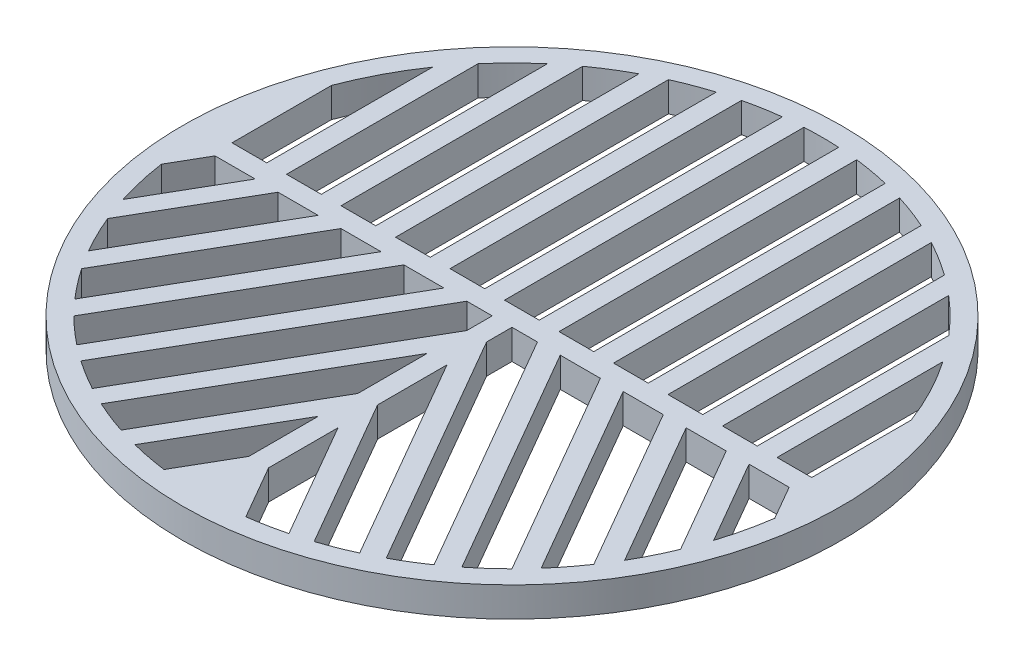
SolidWorks part; units mm, degrees
ref_plane "Front Plane" through (0, 0, 0) normal (0, 0, 1) x (1, 0, 0)
ref_plane "Top Plane" through (0, 0, 0) normal (0, 1, 0) x (1, 0, 0)
ref_plane "Right Plane" through (0, 0, 0) normal (1, 0, 0) x (0, 0, -1)
sketch "Sketch1" plane through (0, 0, 0) normal (0, 1, 0) x (1, 0, 0)
  line L0 (-33.325, 0) -> (33.325, 0) construction
  line L1 (-33.31, 1) -> (33.31, 1) construction
  line L2 (-33.31, -1) -> (33.31, -1) construction
  line L3 (0, 1) -> (0, -1) construction
  line L4 (0, 31.325) -> (0, 33.325) construction
  line L5 (1.7555, 1) -> (1.7555, 31.2758)
  line L6 (1.7555, 1) -> (-1.7555, 1)
  line L7 (-1.7555, 1) -> (-1.7555, 31.2758)
  line L8 (29.31, 1) -> (29.31, 11.0535)
  line L9 (29.31, 1) -> (25.7991, 1)
  line L10 (25.7991, 1) -> (25.7991, 17.7669)
  line L11 (3.7555, 1) -> (7.2664, 1)
  line L12 (9.2664, 1) -> (12.7773, 1)
  line L13 (14.7773, 1) -> (18.2882, 1)
  line L14 (20.2882, 1) -> (23.7991, 1)
  line L15 (3.7555, 1) -> (3.7555, 31.0991)
  line L16 (7.2664, 1) -> (7.2664, 30.4706)
  line L17 (9.2664, 1) -> (9.2664, 29.9231)
  line L18 (12.7773, 1) -> (12.7773, 28.6006)
  line L19 (14.7773, 1) -> (14.7773, 27.6204)
  line L20 (18.2882, 1) -> (18.2882, 25.4322)
  line L21 (20.2882, 1) -> (20.2882, 23.8672)
  line L22 (23.7991, 1) -> (23.7991, 20.3681)
  line L23 (25.7991, 9.3835) -> (23.7991, 9.3835) construction
  line L24 (20.2882, 9.3835) -> (18.2882, 9.3835) construction
  line L25 (14.7773, 9.3835) -> (12.7773, 9.3835) construction
  line L26 (9.2664, 9.3835) -> (7.2664, 9.3835) construction
  line L27 (3.7555, 9.3835) -> (1.7555, 9.3835) construction
  line L28 (0, -1) -> (0, -31.325) construction
  line L29 (1, -1) -> (1, -31.309) construction
  line L30 (1, -13.9187) -> (-1, -13.9187) construction
  line L31 (1, -3.5702) -> (1, -1)
  line L32 (1, -1) -> (3.5702, -1)
  line L33 (3.5702, -1) -> (17.8534, -25.7393)
  line L34 (1, -3.5702) -> (14.8598, -27.5761)
  line L35 (10.9033, -13.7014) -> (7.8628, -15.4569) construction
  line L36 (5.8796, -1) -> (19.47, -24.5393)
  line L37 (9.9336, -1) -> (22.1466, -22.1536)
  line L38 (5.8796, -1) -> (9.9336, -1)
  line L39 (10.9033, -13.7014) -> (12.6354, -12.7014) construction
  line L40 (12.6354, -12.7014) -> (15.6759, -10.946) construction
  line L41 (12.243, -1) -> (23.5748, -20.6273)
  line L42 (16.2971, -1) -> (25.8958, -17.6256)
  line L43 (18.6065, -1) -> (27.1, -15.7113)
  line L44 (22.6605, -1) -> (28.9671, -11.9233)
  line L45 (24.9699, -1) -> (29.8595, -9.4691)
  line L46 (29.024, -1) -> (31.009, -4.4382)
  line L47 (15.6759, -10.946) -> (17.408, -9.946) construction
  line L48 (17.408, -9.946) -> (20.4485, -8.1905) construction
  line L49 (20.4485, -8.1905) -> (22.1806, -7.1905) construction
  line L50 (22.1806, -7.1905) -> (25.2211, -5.4351) construction
  line L51 (25.2211, -5.4351) -> (26.9531, -4.4351) construction
  line L52 (26.9531, -4.4351) -> (29.9937, -2.6796) construction
  line L53 (12.243, -1) -> (16.2971, -1)
  line L54 (18.6065, -1) -> (22.6605, -1)
  line L55 (24.9699, -1) -> (29.024, -1)
  line L56 (1, -7.5702) -> (13.0664, -28.4697)
  line L57 (1, -14.592) -> (9.7605, -29.7656)
  line L58 (1, -18.592) -> (7.7841, -30.3424)
  line L59 (1, -25.6138) -> (4.1388, -31.0504)
  line L60 (11.2632, -21.3466) -> (9.5312, -22.3466) construction
  line L61 (9.5312, -22.3466) -> (6.4906, -24.102) construction
  line L62 (6.4906, -24.102) -> (4.7586, -25.102) construction
  line L63 (4.7586, -25.102) -> (1.7181, -26.8575) construction
  line L64 (1, -7.5702) -> (1, -14.592)
  line L65 (1, -18.592) -> (1, -25.6138)
  line L66 (-29.31, 1) -> (-25.7991, 1)
  line L67 (-20.2882, 1) -> (-23.7991, 1)
  line L68 (-14.7773, 1) -> (-18.2882, 1)
  line L69 (-9.2664, 1) -> (-12.7773, 1)
  line L70 (-3.7555, 1) -> (-7.2664, 1)
  line L71 (-29.31, 1) -> (-29.31, 11.0535)
  line L72 (-25.7991, 1) -> (-25.7991, 17.7669)
  line L73 (-23.7991, 1) -> (-23.7991, 20.3681)
  line L74 (-20.2882, 1) -> (-20.2882, 23.8672)
  line L75 (-18.2882, 1) -> (-18.2882, 25.4322)
  line L76 (-14.7773, 1) -> (-14.7773, 27.6204)
  line L77 (-12.7773, 1) -> (-12.7773, 28.6006)
  line L78 (-9.2664, 1) -> (-9.2664, 29.9231)
  line L79 (-7.2664, 1) -> (-7.2664, 30.4706)
  line L80 (-3.7555, 1) -> (-3.7555, 31.0991)
  line L81 (-24.9699, -1) -> (-29.024, -1)
  line L82 (-18.6065, -1) -> (-22.6605, -1)
  line L83 (-12.243, -1) -> (-16.2971, -1)
  line L84 (-5.8796, -1) -> (-9.9336, -1)
  line L85 (-1, -1) -> (-3.5702, -1)
  line L86 (-1, -3.5702) -> (-1, -1)
  line L87 (-1, -7.5702) -> (-1, -14.592)
  line L88 (-1, -18.592) -> (-1, -25.6138)
  line L89 (-29.024, -1) -> (-31.009, -4.4382)
  line L90 (-24.9699, -1) -> (-29.8595, -9.4691)
  line L91 (-22.6605, -1) -> (-28.9671, -11.9233)
  line L92 (-18.6065, -1) -> (-27.1, -15.7113)
  line L93 (-16.2971, -1) -> (-25.8958, -17.6256)
  line L94 (-12.243, -1) -> (-23.5748, -20.6273)
  line L95 (-9.9336, -1) -> (-22.1466, -22.1536)
  line L96 (-5.8796, -1) -> (-19.47, -24.5393)
  line L97 (-3.5702, -1) -> (-17.8534, -25.7393)
  line L98 (-1, -3.5702) -> (-14.8598, -27.5761)
  line L99 (-1, -7.5702) -> (-13.0664, -28.4697)
  line L100 (-1, -14.592) -> (-9.7605, -29.7656)
  line L101 (-1, -18.592) -> (-7.7841, -30.3424)
  line L102 (-1, -25.6138) -> (-4.1388, -31.0504)
  circle A0 centre (0, 0) radius 33.325
  circle A1 centre (0, 0) radius 31.325 construction
  arc A2 (-1.7555, 31.2758) -> (1.7555, 31.2758) centre (0, 0) cw
  arc A3 (25.7991, 17.7669) -> (29.31, 11.0535) centre (0, 0) cw
  arc A4 (3.7555, 31.0991) -> (7.2664, 30.4706) centre (0, 0) cw
  arc A5 (9.2664, 29.9231) -> (12.7773, 28.6006) centre (0, 0) cw
  arc A6 (14.7773, 27.6204) -> (18.2882, 25.4322) centre (0, 0) cw
  arc A7 (20.2882, 23.8672) -> (23.7991, 20.3681) centre (0, 0) cw
  arc A8 (17.8534, -25.7393) -> (14.8598, -27.5761) centre (0, 0) cw
  arc A9 (31.009, -4.4382) -> (29.8595, -9.4691) centre (0, 0) cw
  arc A10 (28.9671, -11.9233) -> (27.1, -15.7113) centre (0, 0) cw
  arc A11 (25.8958, -17.6256) -> (23.5748, -20.6273) centre (0, 0) cw
  arc A12 (22.1466, -22.1536) -> (19.47, -24.5393) centre (0, 0) cw
  arc A13 (13.0664, -28.4697) -> (9.7605, -29.7656) centre (0, 0) cw
  arc A14 (7.7841, -30.3424) -> (4.1388, -31.0504) centre (0, 0) cw
  arc A15 (-3.7555, 31.0991) -> (-7.2664, 30.4706) centre (0, 0) ccw
  arc A16 (-9.2664, 29.9231) -> (-12.7773, 28.6006) centre (0, 0) ccw
  arc A17 (-14.7773, 27.6204) -> (-18.2882, 25.4322) centre (0, 0) ccw
  arc A18 (-20.2882, 23.8672) -> (-23.7991, 20.3681) centre (0, 0) ccw
  arc A19 (-25.7991, 17.7669) -> (-29.31, 11.0535) centre (0, 0) ccw
  arc A20 (-7.7841, -30.3424) -> (-4.1388, -31.0504) centre (0, 0) ccw
  arc A21 (-13.0664, -28.4697) -> (-9.7605, -29.7656) centre (0, 0) ccw
  arc A22 (-17.8534, -25.7393) -> (-14.8598, -27.5761) centre (0, 0) ccw
  arc A23 (-22.1466, -22.1536) -> (-19.47, -24.5393) centre (0, 0) ccw
  arc A24 (-25.8958, -17.6256) -> (-23.5748, -20.6273) centre (0, 0) ccw
  arc A25 (-28.9671, -11.9233) -> (-27.1, -15.7113) centre (0, 0) ccw
  arc A26 (-31.009, -4.4382) -> (-29.8595, -9.4691) centre (0, 0) ccw
  point P13 (0, 0)
  point P61 (0, -13.9187)
  dimension "D1" = 66.65
  dimension "D3" = 2
  dimension "D4" = 4
  dimension "D5" = 30
  dimension "D2" = 2
extrude "Boss-Extrude1" add sketch "Sketch1" along normal blind 3
